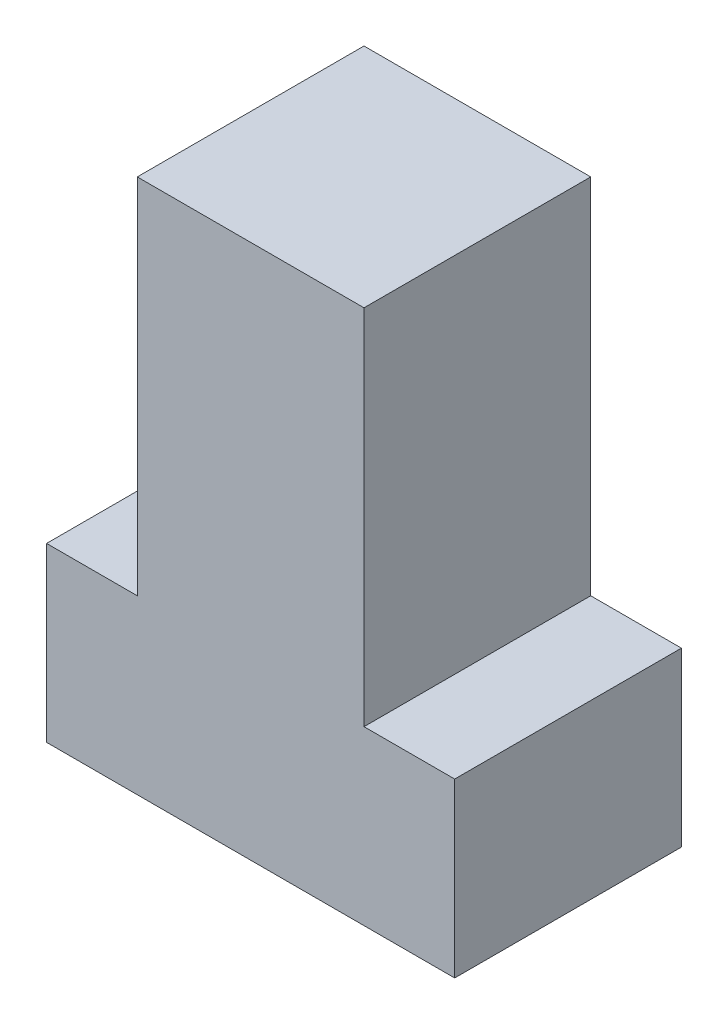
SolidWorks part; units mm, degrees
ref_plane "Front Plane" through (0, 0, 0) normal (0, 0, 1) x (1, 0, 0)
ref_plane "Top Plane" through (0, 0, 0) normal (0, 1, 0) x (1, 0, 0)
ref_plane "Right Plane" through (0, 0, 0) normal (1, 0, 0) x (0, 0, -1)
sketch "Sketch2" plane through (0, 0, 0) normal (0, 0, 1) x (1, 0, 0)
  line L0 (38.9911, -6.6199) -> (47.9911, -6.6199)
  line L5 (47.9911, -6.6199) -> (47.9911, -2.8199)
  line L11 (38.9911, -2.8199) -> (38.9911, -6.6199)
  line L12 (38.9911, -2.8199) -> (40.9911, -2.8199)
  line L13 (40.9911, -2.8199) -> (40.9911, 5.1801)
  line L14 (40.9911, 5.1801) -> (45.9911, 5.1801)
  line L15 (45.9911, 5.1801) -> (45.9911, -2.8199)
  line L16 (45.9911, -2.8199) -> (47.9911, -2.8199)
  dimension "D1" = 3.8
  dimension "D2" = 9
  dimension "D3" = 5
  dimension "D4" = 8
extrude "Boss-Extrude1" add sketch "Sketch2" along normal blind 5
equation "\"Big_base_height\"= 5cm"
equation "\"small_base_height\"= 5cm"
equation "\"length_base\"= 40cm"
equation "\"draft\"= atn ( \"length_base\" / ( 0.5 * 0.8 * \"Big_base_height\" ) ) * 1deg"
equation "\"length_ext\"= \"target_ext\" - \"hub_radius\" - \"length_base\""
equation "\"diff_radius\"= 0.5 * ( \"Big_base_height\" * 0.8 - \"small_base_height\" * 0.8 )"
equation "\"draft_angle_2\"= atn ( \"diff_radius\" / \"length_base\" ) * 1deg"
equation "\"hub_radius\"= 15cm"
equation "\"target_ext\"= 75cm"
equation "\"draft_angle\"= IIF ( ( atn ( \"diff_radius\" / \"length_base\" ) * 1deg ) < 0.5deg , 0deg , atn ( \"diff_radius\" / \"length_base\" ) * 1deg )"
equation "\"shaft_length\"= \"length_ext\" * 1.10"
equation "\"shaft_radius\"= \"small_base_height\" * 0.5 * 0.8"
equation "\"shaft_hollow\"= 0.75 * ( \"shaft_radius\" - \"key_deep\" )"
equation "\"key_width_t\"= 5mm"
equation "\"key_height_t\"= 9mm"
equation "\"key_base_w\"= 0.9"
equation "\"key_base_h\"= 0.5"
equation "\"key_deep\"= 8mm"
equation "\"key slot\"= 4mm"
equation "\"hub_thick\"= \"Big_base_height\" * 2"
equation "\"insert_hub\"= \"Big_base_height\" * 1.05"
equation "\"insert_thick\"= 1cm"
equation "\"hallow_hub\"= \"hub_radius\" * 0.75"
equation "\"offset_hub_base_hallow\"= 10mm"
equation "\"D1@Sketch2\"=\"key slot\"*0.95"
equation "\"D3@Sketch2\"=\"key_width_t\""
equation "\"D4@Sketch2\"=\"key_deep\""
equation "\"D1@Boss-Extrude1\"=\"key_width_t\""
